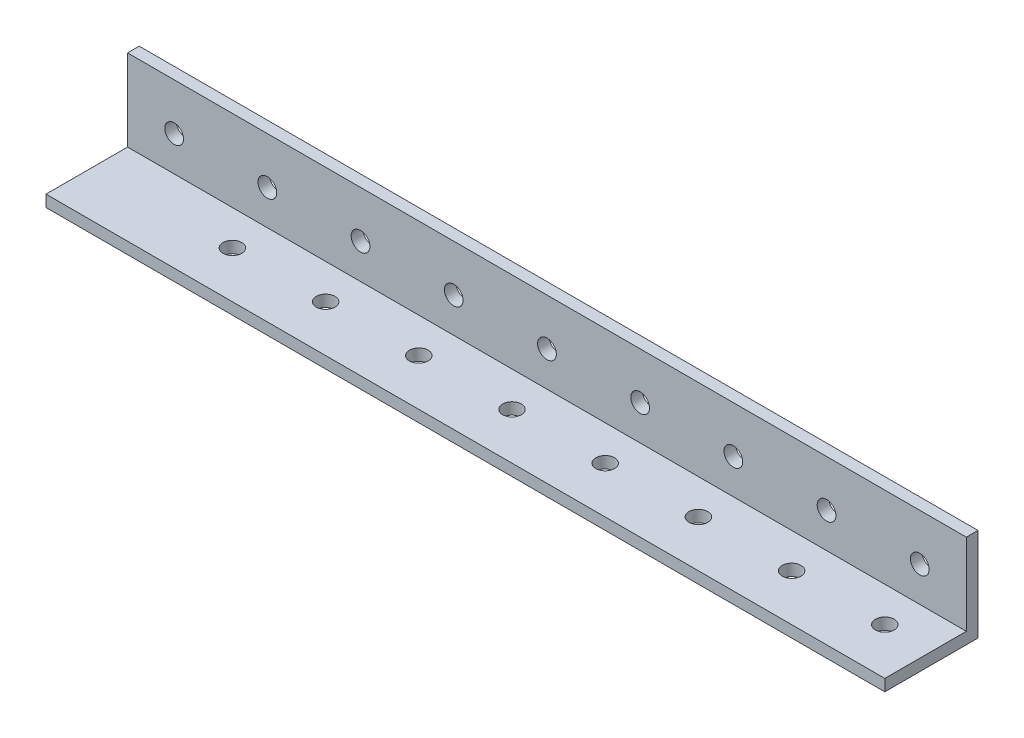
SolidWorks part; units mm, degrees
ref_plane "Front Plane" through (0, 0, 0) normal (0, 0, 1) x (1, 0, 0)
ref_plane "Top Plane" through (0, 0, 0) normal (0, 1, 0) x (1, 0, 0)
ref_plane "Right Plane" through (0, 0, 0) normal (1, 0, 0) x (0, 0, -1)
ref_plane "Plane1" through (0, 101.6, 0) normal (0, 1, 0) x (1, 0, 0)
sketch "Sketch1" plane through (0, 101.6, 0) normal (0, 1, 0) x (1, 0, 0)
  line L0 (0, 0) -> (0, -25.4)
  line L1 (0, -25.4) -> (228.6, -25.4)
  line L2 (228.6, -25.4) -> (228.6, 0)
  line L3 (228.6, 0) -> (0, 0)
extrude "Boss-Extrude1" add sketch "Sketch1" against normal blind 25.4
sketch "Sketch2" plane through (228.6, 0, 0) normal (1, 0, 0) x (0, 0, -1)
  line L0 (-25.4, 101.6) -> (-25.4, 79.375)
  line L1 (-25.4, 79.375) -> (-3.175, 79.375)
  line L2 (-3.175, 79.375) -> (-3.175, 101.6)
  line L3 (-3.175, 101.6) -> (-25.4, 101.6)
extrude "Cut-Extrude1" cut sketch "Sketch2" against normal through all
hole_wizard "#7 (0.201) Diameter Hole1" positions "Sketch4" profile "Sketch3" hole size "#7" standard "ANSI Inch"
sketch "Sketch4" plane through (0, 76.2, 0) normal (0, -1, 0) x (1, 0, 0)
  point P0 (-12.7, -12.7)
  point P1 (38.1, 12.7)
  point P2 (63.5, 12.7)
  point P3 (88.9, 12.7)
  point P4 (114.3, 12.7)
  point P5 (139.7, 12.7)
  point P6 (165.1, 12.7)
  point P7 (190.5, 12.7)
  point P8 (215.9, 12.7)
sketch "Sketch3" plane through (-12.7, 76.2, -12.7) normal (1, 0, 0) x (0, 0, -1)
  line L0 (0, 0) -> (0, 25.4)
  line L1 (0, 25.4) -> (2.5527, 25.4)
  line L2 (2.5527, 25.4) -> (2.5527, 0)
  line L5 (2.5527, 0) -> (0, 0)
  line L11 (0, -6.35) -> (0, 107.95) construction
  dimension "Thru Hole Dia." = 5.1054
  dimension "Thru Hole Depth" = 25.4
hole_wizard "#7 (0.201) Diameter Hole2" positions "Sketch6" profile "Sketch5" hole size "#7" standard "ANSI Inch"
sketch "Sketch6" plane through (0, 0, 3.175) normal (0, 0, 1) x (1, 0, 0)
  point P0 (12.7, 88.9)
  point P1 (38.1, 88.9)
  point P2 (63.5, 88.9)
  point P3 (88.9, 88.9)
  point P4 (114.3, 88.9)
  point P5 (139.7, 88.9)
  point P6 (165.1, 88.9)
  point P7 (190.5, 88.9)
  point P8 (215.9, 88.9)
sketch "Sketch5" plane through (12.7, 88.9, 3.175) normal (1, 0, 0) x (0, -1, 0)
  line L0 (0, 0) -> (0, 3.175)
  line L1 (0, 3.175) -> (2.5527, 3.175)
  line L2 (2.5527, 3.175) -> (2.5527, 0)
  line L5 (2.5527, 0) -> (0, 0)
  line L11 (0, -6.35) -> (0, 107.95) construction
  dimension "Thru Hole Dia." = 5.1054
  dimension "Thru Hole Depth" = 3.175
